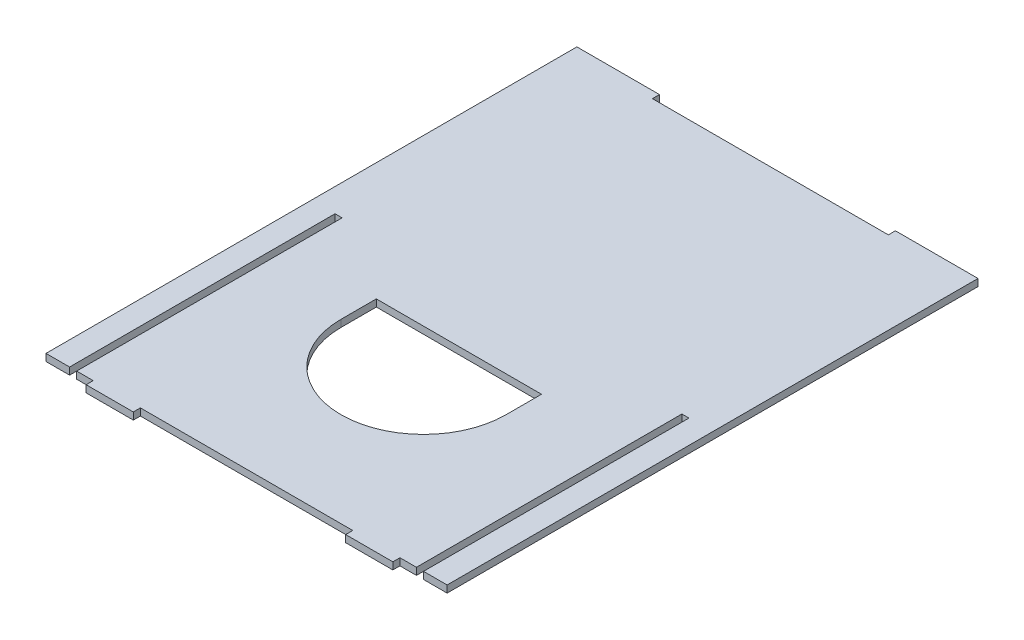
SolidWorks part; units mm, degrees
ref_plane "Front Plane" through (0, 0, 0) normal (0, 0, 1) x (1, 0, 0)
ref_plane "Top Plane" through (0, 0, 0) normal (0, 1, 0) x (1, 0, 0)
ref_plane "Right Plane" through (0, 0, 0) normal (1, 0, 0) x (0, 0, -1)
sketch "Sketch1" plane through (0, 0, 0) normal (0, 1, 0) x (1, 0, 0)
  line L0 (300, 0) -> (300, -6)
  line L2 (0, 0) -> (0, 450)
  line L3 (0, 450) -> (340, 450)
  line L4 (340, 0) -> (340, 450)
  line L5 (300, -6) -> (260, -6)
  line L6 (260, -6) -> (260, 0)
  line L7 (40, 0) -> (40, -6)
  line L8 (40, -6) -> (80, -6)
  line L9 (80, -6) -> (80, 0)
  line L10 (40, 0) -> (0, 0)
  line L11 (80, 0) -> (260, 0)
  line L12 (300, 0) -> (340, 0)
  point P11 (80, -3)
  dimension "D1" = 340
  dimension "D2" = 450
  dimension "D3" = 40
  dimension "D4" = 6
  dimension "D5" = 40
  dimension "D6" = 180
extrude "Boss-Extrude1" add sketch "Sketch1" along normal blind 6
sketch "Sketch2" plane through (0, 6, 0) normal (0, 1, 0) x (1, 0, 0)
  line L1 (20, 0) -> (26, 0)
  line L2 (20, 0) -> (20, 225)
  line L3 (20, 225) -> (26, 225)
  line L4 (26, 0) -> (26, 225)
  line L5 (0, 450) -> (0, 0) construction
  line L6 (0, 0) -> (40, 0) construction
  line L7 (0, 0) -> (40, 0) construction
  point P4 (0, 0)
  dimension "D1" = 225
  dimension "D2" = 6
  dimension "D3" = 20
extrude "Cut-Extrude1" cut sketch "Sketch2" against normal blind 6
pattern_linear "LPattern1" count 2 spacing 294 along (1, 0, 0) of "Cut-Extrude1"
sketch "Sketch3" plane through (0, 6, 0) normal (0, 1, 0) x (1, 0, 0)
  line L0 (100, 150) -> (100, 180)
  line L3 (340, 450) -> (0, 450) construction
  line L4 (70, 450) -> (270, 450)
  line L5 (70, 450) -> (70, 444)
  line L6 (70, 444) -> (270, 444)
  line L7 (270, 450) -> (270, 444)
  line L9 (240, 150) -> (240, 180)
  line L10 (100, 180) -> (240, 180)
  line L12 (0, 450) -> (0, 0) construction
  line L13 (80, 0) -> (260, 0) construction
  arc A1 (100, 150) -> (240, 150) centre (170, 150) ccw
  point P6 (0, 0)
  point P14 (170, 450)
  dimension "D1" = 200
  dimension "D2" = 70
  dimension "D3" = 150
  dimension "D4" = 170
  dimension "D6" = 140
  dimension "D5" = 6
  dimension "D8" = 30
extrude "Cut-Extrude2" cut sketch "Sketch3" against normal blind 6
